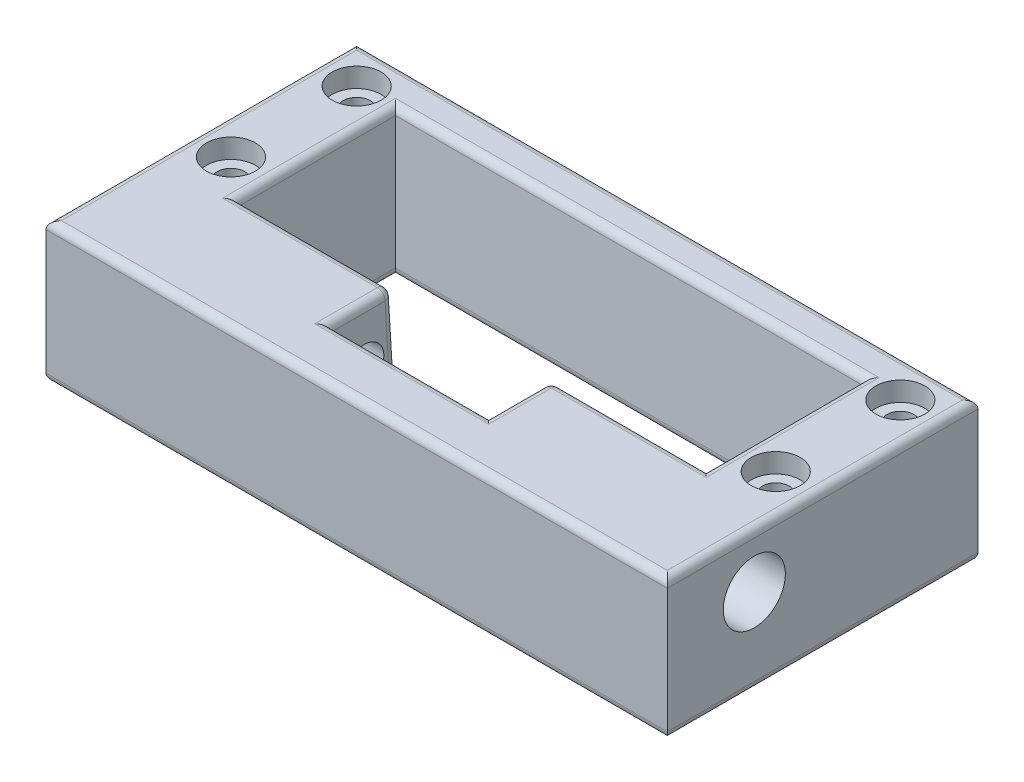
SolidWorks part; units mm, degrees
ref_plane "正面" through (0, 0, 0) normal (0, 0, 1) x (1, 0, 0)
ref_plane "平面" through (0, 0, 0) normal (0, 1, 0) x (1, 0, 0)
ref_plane "右側面" through (0, 0, 0) normal (1, 0, 0) x (0, 0, -1)
ref_plane "平面1" through (0, 18, 0) normal (0, 1, 0) x (1, 0, 0)
sketch "ｽｹｯﾁ1" plane through (0, 18, 0) normal (0, 1, 0) x (1, 0, 0)
  line L0 (-40, -20) -> (40, -20)
  line L1 (40, -20) -> (40, 20)
  line L2 (40, 20) -> (-40, 20)
  line L3 (-40, 20) -> (-40, -20)
extrude "ﾎﾞｽ - 押し出し1" add sketch "ｽｹｯﾁ1" against normal blind 18
sketch "ｽｹｯﾁ2" plane through (0, 0, 0) normal (0, -1, 0) x (1, 0, 0)
  line L0 (-10.2, 13.2) -> (-10.2, 4.0991)
  line L1 (-10.2, 4.0991) -> (-29.0991, 4.0991)
  line L2 (-29.0991, 4.0991) -> (-29.0991, -14.0991)
  line L3 (-29.0991, -14.0991) -> (29.0991, -14.0991)
  line L4 (29.0991, -14.0991) -> (29.0991, 4.0991)
  line L5 (29.0991, 4.0991) -> (10.2, 4.0991)
  line L6 (10.2, 4.0991) -> (10.2, 13.2)
  line L7 (10.2, 13.2) -> (-10.2, 13.2)
extrude "ｶｯﾄ - 押し出し1" cut sketch "ｽｹｯﾁ2" against normal through all
draft "抜き勾配1" type of draft neutral plane draft angle 3.5 faces to draft 5 face at (-19.6495, 9, 4.0991) face at (-29.0991, 9, -5) face at (0, 9, -14.0991) face at (29.0991, 9, -5) face at (19.6495, 9, 4.0991) neutral plane through (0, 0, 0) neutral plane normal (0, -1, 0) reverse direction yes parameters "D1"=3.5
hole_wizard "Ø3.5 (3.5) 直径の穴1" positions "ｽｹｯﾁ4" profile "ｽｹｯﾁ3" hole size "Ø3.5" standard "Ansi Metric"
sketch "ｽｹｯﾁ4" plane through (0, 18, 0) normal (0, 1, 0) x (1, 0, 0)
  point P0 (-35.1863, -1)
  point P1 (-35, 15)
  point P2 (34.9582, -1)
  point P3 (35, 15)
sketch "ｽｹｯﾁ3" plane through (-35.1863, 18, 1) normal (1, 0, 0) x (0, 0, 1)
  line L0 (0, 0) -> (0, 18)
  line L1 (0, 18) -> (1.75, 18)
  line L2 (1.75, 18) -> (1.75, 0)
  line L5 (1.75, 0) -> (0, 0)
  line L11 (0, -6.35) -> (0, 107.95) construction
  dimension "通し穴の直径" = 3.5
  dimension "通し穴の深さ" = 18
hole_wizard "M8x1.0 ねじ穴1" positions "ｽｹｯﾁ6" profile "ｽｹｯﾁ5" tap size "M8x1.0" standard "Ansi Metric"
sketch "ｽｹｯﾁ6" plane through (40, 0, 0) normal (1, 0, 0) x (0, 0, -1)
  point P0 (-8.8, 11)
sketch "ｽｹｯﾁ5" plane through (40, 11, 8.8) normal (0, 1, 0) x (0, 0, -1)
  line L0 (0, 0) -> (0, 29.8)
  line L1 (0, 29.8) -> (2.5, 29.8)
  line L3 (2.5, 29.8) -> (2.5, 22)
  line L4 (2.5, 22) -> (4, 22)
  line L5 (4, 22) -> (4, 0)
  line L7 (4, 0) -> (0, 0)
  line L11 (0, -6.35) -> (0, 107.95) construction
  dimension "次ｻｰﾌｪｽまでのねじ下穴ﾄﾞﾘﾙ直径" = 5
  dimension "次ｻｰﾌｪｽまでのねじ下穴ﾄﾞﾘﾙの深さ" = 29.8
  dimension "ねじ山の主要直径" = 8
  dimension "ねじ山の深さ" = 22
hole_wizard "M8x1.0 ねじ穴2" positions "ｽｹｯﾁ8" profile "ｽｹｯﾁ7" tap size "M8x1.0" standard "Ansi Metric"
sketch "ｽｹｯﾁ8" plane through (-40, 0, 0) normal (-1, 0, 0) x (0, 0, 1)
  point P0 (8.8, 11)
sketch "ｽｹｯﾁ7" plane through (-40, 11, 8.8) normal (0, 1, 0) x (0, 0, 1)
  line L0 (0, 0) -> (0, 80)
  line L1 (0, 80) -> (2.5, 80)
  line L3 (2.5, 80) -> (2.5, 22)
  line L4 (2.5, 22) -> (4, 22)
  line L5 (4, 22) -> (4, 0)
  line L7 (4, 0) -> (0, 0)
  line L11 (0, -6.35) -> (0, 107.95) construction
  dimension "次ｻｰﾌｪｽまでのねじ下穴ﾄﾞﾘﾙ直径" = 5
  dimension "次ｻｰﾌｪｽまでのねじ下穴ﾄﾞﾘﾙの深さ" = 80
  dimension "ねじ山の主要直径" = 8
  dimension "ねじ山の深さ" = 22
fillet "ﾌｨﾚｯﾄ1" radius 1 26 edges at (40, 0, 0) (0, 0, -20) (0, 0, 20) (-40, 0, 0) (30.2, 18, -5) (0, 18, -15.2) (20.2, 18, 5.2) (10.2, 18, 9.2) (0, 18, 13.2) (-30.2, 18, -5) (10.2, 0, 8.6495) (10.2, 9, 4.6495) (0, 0, 13.2) (-10.2, 18, 9.2) (-20.2, 18, 5.2) (19.6495, 0, 4.0991) (-10.2, 0, 8.6495) (-10.2, 9, 4.6495) (29.0991, 0, -5) (-19.6495, 0, 4.0991) (0, 0, -14.0991) (-29.0991, 0, -5) (0, 18, -20) (40, 18, 0) (-40, 18, 0) (0, 18, 20)
sketch "ｽｹｯﾁ9" plane through (0, 18, 0) normal (0, 1, 0) x (1, 0, 0)
  line L0 (0, 19) -> (0, -19) construction
  line L1 (39, 19) -> (-39, 19) construction
  line L2 (-39, -19) -> (39, -19) construction
  circle A0 centre (35, 15) radius 3.15
  circle A1 centre (34.9582, -1) radius 3.15
  circle A2 centre (-35, 15) radius 3.15
  circle A3 centre (-35.1863, -1) radius 3.15
  dimension "D1" = 6.3
  dimension "D2" = 6.3
  dimension "D3" = 6.3
  dimension "D4" = 6.3
extrude "ｶｯﾄ - 押し出し2" cut sketch "ｽｹｯﾁ9" against normal blind 2.5
